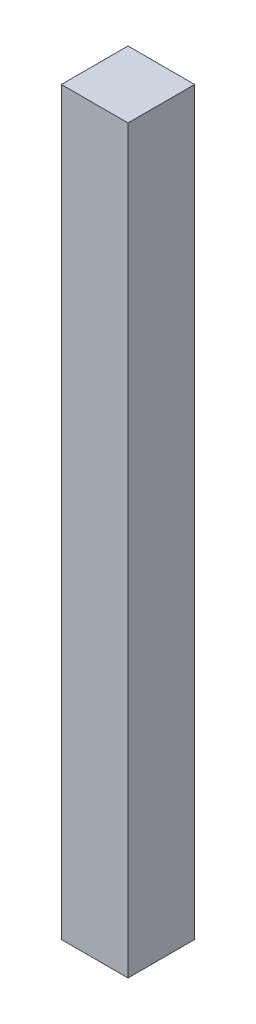
SolidWorks part; units mm, degrees
ref_plane "Front Plane" through (0, 0, 0) normal (0, 0, 1) x (1, 0, 0)
ref_plane "Top Plane" through (0, 0, 0) normal (0, 1, 0) x (1, 0, 0)
ref_plane "Right Plane" through (0, 0, 0) normal (1, 0, 0) x (0, 0, -1)
other "Configuration Table"
sketch "Sketch1" plane through (0, 0, 0) normal (0, 0, 1) x (1, 0, 0)
  line L1 (637, 490) -> (655, 490)
  line L2 (637, 490) -> (637, 690)
  line L3 (637, 690) -> (655, 690)
  line L4 (655, 490) -> (655, 690)
extrude "TOPPING_klape_alt1_gazli_amortisor_2_1" add sketch "Sketch1" along normal blind 18 from offset 8 separate body
